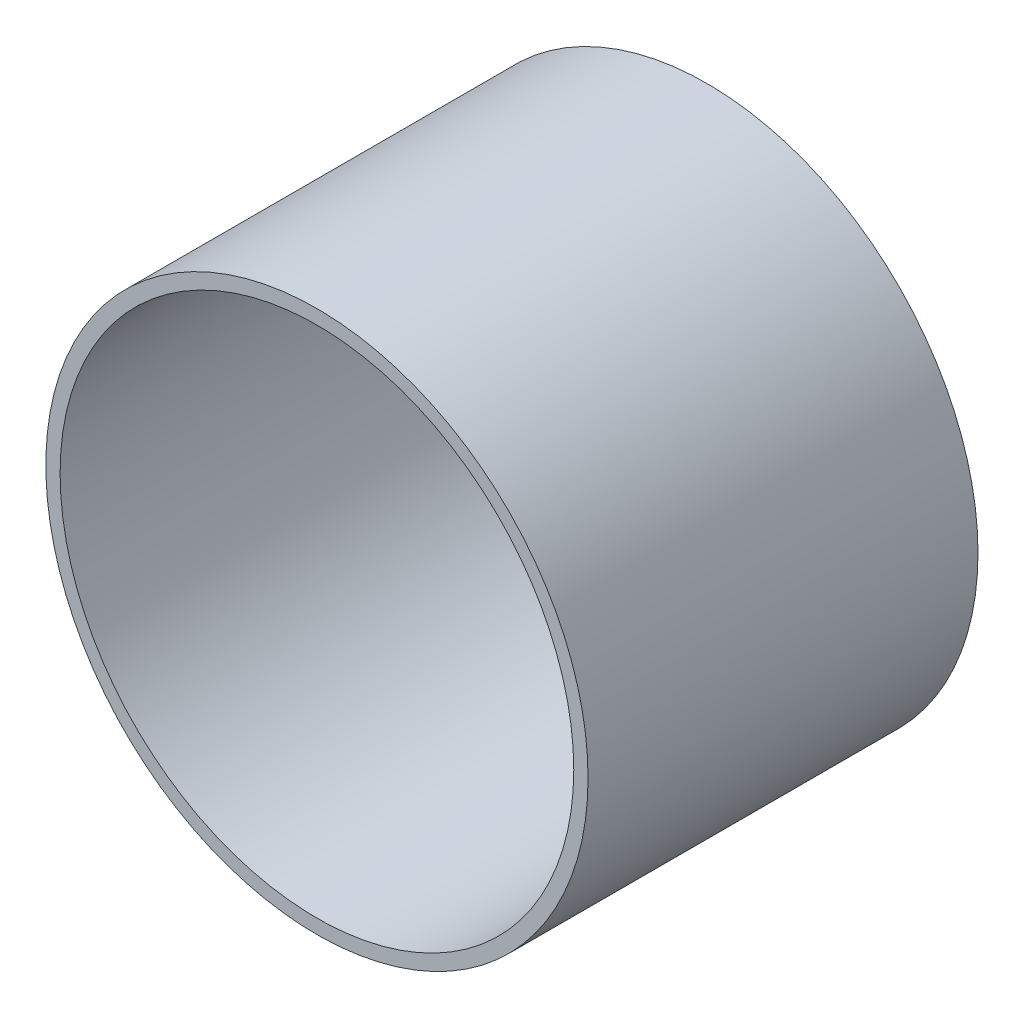
SolidWorks part; units mm, degrees
ref_plane "Front Plane" through (0, 0, 0) normal (0, 0, 1) x (1, 0, 0)
ref_plane "Top Plane" through (0, 0, 0) normal (0, 1, 0) x (1, 0, 0)
ref_plane "Right Plane" through (0, 0, 0) normal (1, 0, 0) x (0, 0, -1)
sketch "Sketch1" plane through (0, 0, 0) normal (0, 0, 1) x (1, 0, 0)
  circle A0 centre (0, 0) radius 57.15
  circle A1 centre (0, 0) radius 54.1401
  dimension "D1" = 114.3
  dimension "D2" = 108.2802
extrude "Boss-Extrude1" add sketch "Sketch1" along normal mid plane 82.2 contours A1 | A0
